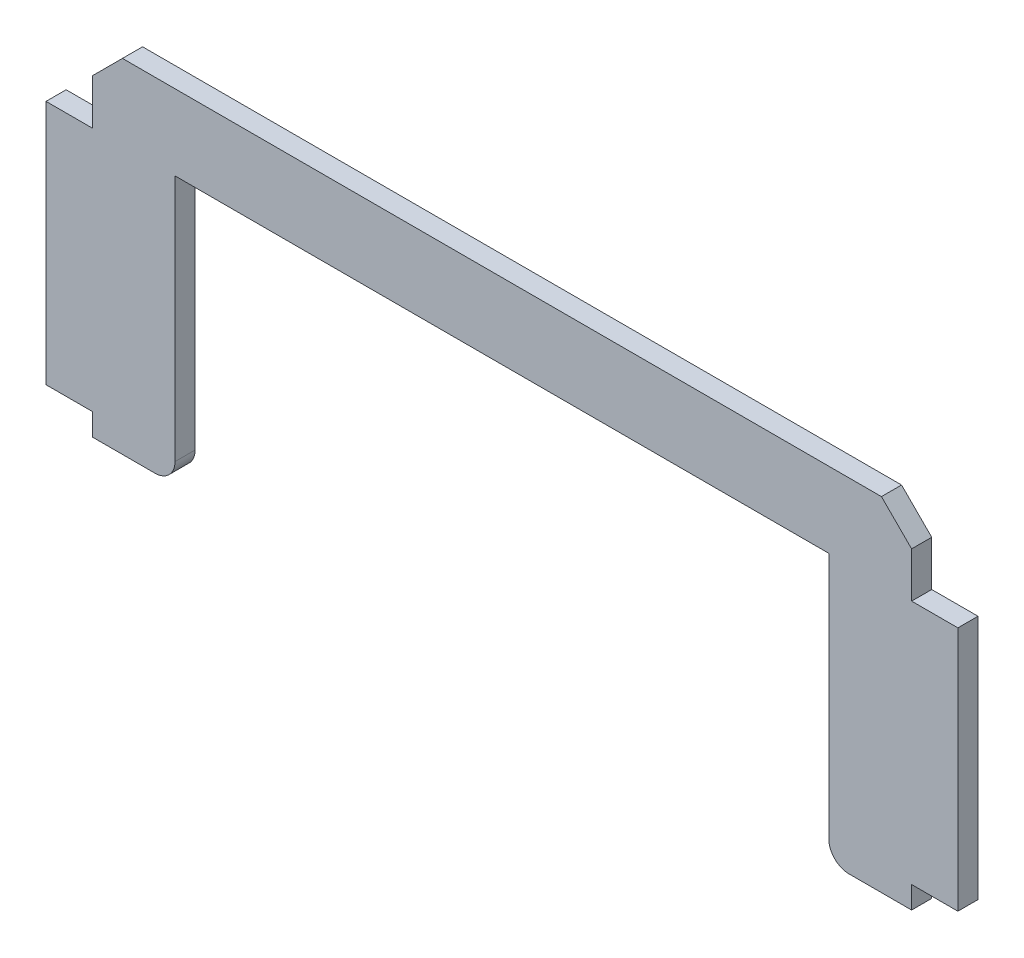
SolidWorks part; units mm, degrees
ref_plane "Front Plane" through (0, 0, 0) normal (0, 0, 1) x (1, 0, 0)
ref_plane "Top Plane" through (0, 0, 0) normal (0, 1, 0) x (1, 0, 0)
ref_plane "Right Plane" through (0, 0, 0) normal (1, 0, 0) x (0, 0, -1)
sketch "Sketch1" plane through (0, 0, 0) normal (0, 0, 1) x (1, 0, 0)
  line L0 (5.842, 0) -> (16.2941, 0)
  line L1 (16.2941, 0) -> (16.2941, 33.782)
  line L2 (16.2941, 33.782) -> (98.8441, 33.782)
  line L3 (98.8441, 33.782) -> (98.8441, 0)
  line L4 (98.8441, 0) -> (109.2962, 0)
  line L5 (109.2962, 0) -> (109.2962, 2.794)
  line L6 (109.2962, 2.794) -> (115.1382, 2.794)
  line L7 (115.1382, 2.794) -> (115.1382, 33.782)
  line L8 (115.1382, 33.782) -> (109.2962, 33.782)
  line L9 (109.2962, 33.782) -> (109.2962, 43.307)
  line L10 (109.2962, 43.307) -> (5.842, 43.307)
  line L11 (5.842, 43.307) -> (5.842, 33.782)
  line L12 (5.842, 33.782) -> (0, 33.782)
  line L13 (0, 33.782) -> (0, 2.794)
  line L14 (0, 2.794) -> (5.842, 2.794)
  line L15 (5.842, 2.794) -> (5.842, 0)
  dimension "D1" = 115.1382
  dimension "D2" = 30.988
  dimension "D3" = 30.988
  dimension "D4" = 9.525
  dimension "D5" = 9.525
  dimension "D6" = 2.794
  dimension "D7" = 16.2941
  dimension "D8" = 5.842
  dimension "D9" = 9.525
  dimension "D10" = 5.842
  dimension "D11" = 5.842
  dimension "D12" = 5.842
  dimension "D13" = 16.2941
extrude "Boss-Extrude1" add sketch "Sketch1" along normal blind 2.54
chamfer "Chamfer1" distance 3.81 angle 45 2 edges at (109.2962, 43.307, 1.27) (5.842, 43.307, 1.27)
fillet "Fillet1" radius 2.54 2 edges at (16.2941, 0, 1.27) (98.8441, 0, 1.27)
